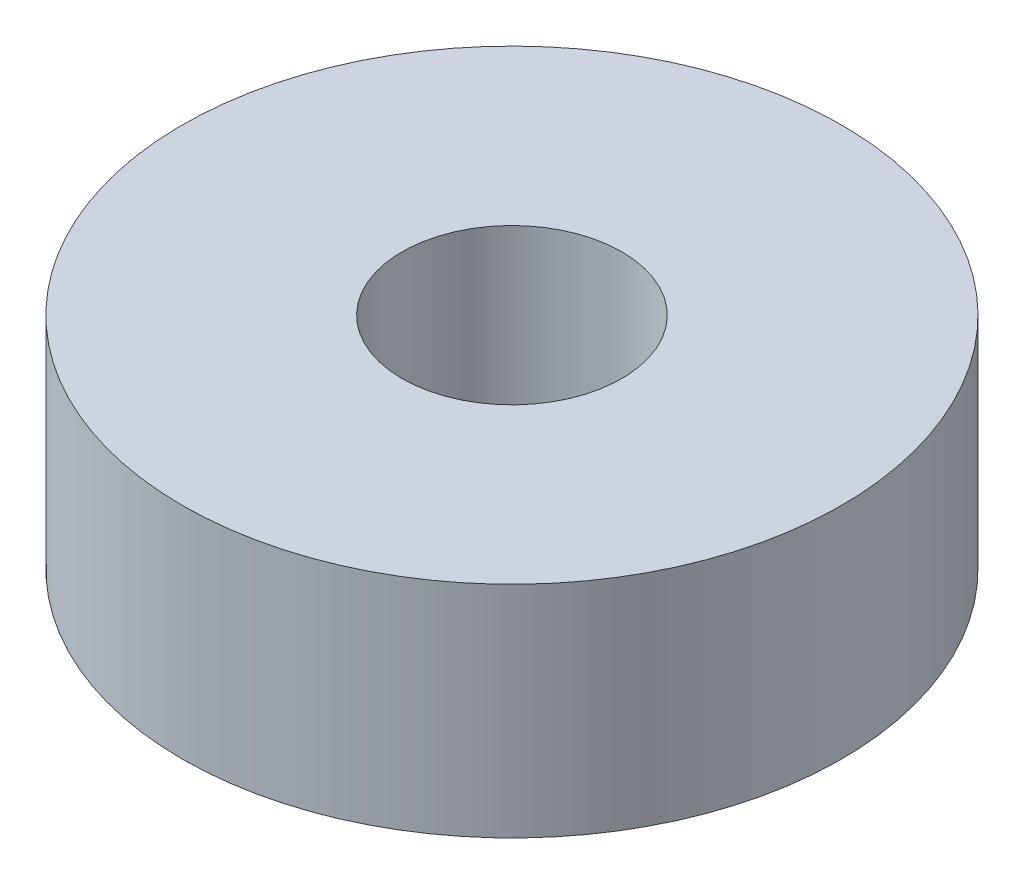
SolidWorks part; units mm, degrees
ref_plane "Front Plane" through (0, 0, 0) normal (0, 0, 1) x (1, 0, 0)
ref_plane "Top Plane" through (0, 0, 0) normal (0, 1, 0) x (1, 0, 0)
ref_plane "Right Plane" through (0, 0, 0) normal (1, 0, 0) x (0, 0, -1)
sketch "Sketch1" plane through (0, 0, 0) normal (0, 1, 0) x (1, 0, 0)
  circle A0 centre (8.3772, 0) radius 6
  circle A1 centre (8.3772, 0) radius 2
  dimension "D1" = 12
  dimension "D2" = 4
extrude "Boss-Extrude1" add sketch "Sketch1" along normal blind 4
